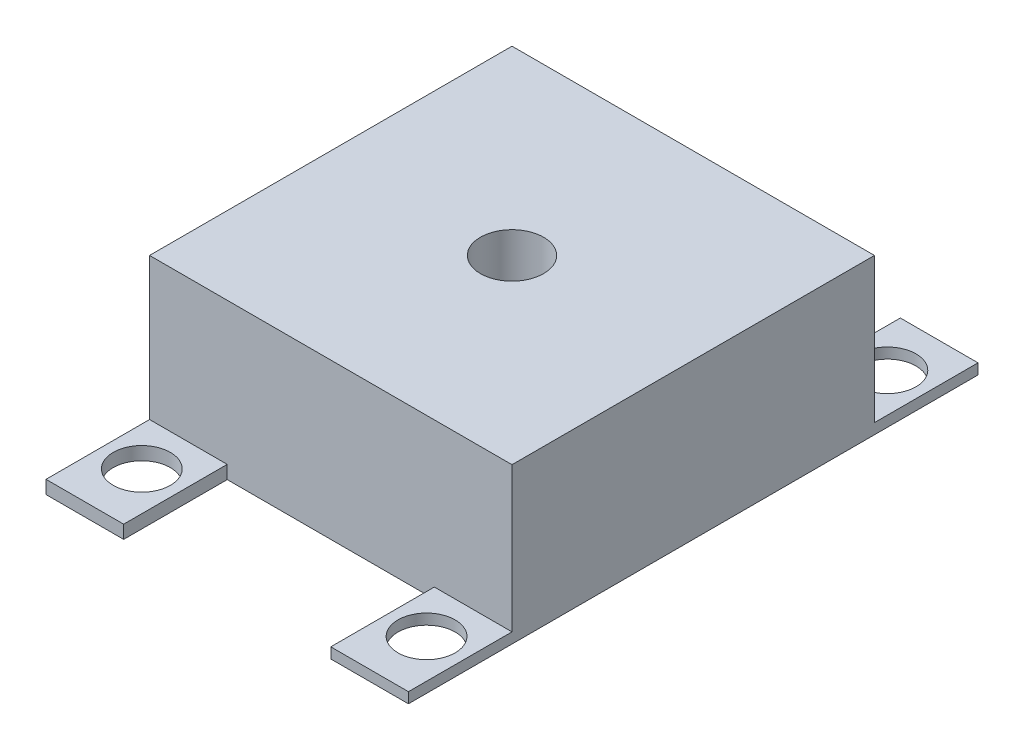
SolidWorks part; units mm, degrees
ref_plane "Front Plane" through (0, 0, 0) normal (0, 0, 1) x (1, 0, 0)
ref_plane "Top Plane" through (0, 0, 0) normal (0, 1, 0) x (1, 0, 0)
ref_plane "Right Plane" through (0, 0, 0) normal (1, 0, 0) x (0, 0, -1)
sketch "Sketch2" plane through (0, 0, 0) normal (0, 1, 0) x (1, 0, 0)
  line L1 (-17.5, 17.5) -> (17.5, 17.5)
  line L2 (-17.5, 17.5) -> (-17.5, -17.5)
  line L3 (-17.5, -17.5) -> (17.5, -17.5)
  line L4 (17.5, 17.5) -> (17.5, -17.5)
  line L5 (-17.5, 17.5) -> (17.5, -17.5) construction
  line L6 (-17.5, -17.5) -> (17.5, 17.5) construction
  point P0 (0, 0)
  dimension "D1" = 35
  dimension "D2" = 35
extrude "Boss-Extrude1" add sketch "Sketch2" along normal blind 10 contours L2 L1 L4 L3
sketch "Sketch3" plane through (0, 10, 0) normal (0, 1, 0) x (1, 0, 0)
  line L1 (-17.5, 17.5) -> (17.5, 17.5)
  line L2 (-17.5, 17.5) -> (-17.5, -17.5)
  line L3 (-17.5, -17.5) -> (17.5, -17.5)
  line L4 (17.5, 17.5) -> (17.5, -17.5)
  line L5 (-17.5, 17.5) -> (17.5, -17.5) construction
  line L6 (-17.5, -17.5) -> (17.5, 17.5) construction
  line L7 (-15, 15) -> (15, 15)
  line L8 (-15, 15) -> (-15, -15)
  line L9 (-15, -15) -> (15, -15)
  line L10 (15, 15) -> (15, -15)
  line L11 (-15, 15) -> (15, -15) construction
  line L12 (-15, -15) -> (15, 15) construction
  point P0 (0, 0)
  point P7 (0, 0)
  dimension "D1" = 30
extrude "Boss-Extrude2" add sketch "Sketch3" along normal blind 15 separate body
sketch "Sketch4" plane through (0, 25, 0) normal (0, 1, 0) x (1, 0, 0)
  line L1 (-17.5, 17.5) -> (17.5, 17.5)
  line L2 (-17.5, 17.5) -> (-17.5, -17.5)
  line L3 (-17.5, -17.5) -> (17.5, -17.5)
  line L4 (17.5, 17.5) -> (17.5, -17.5)
  line L5 (-17.5, 17.5) -> (17.5, -17.5) construction
  line L6 (-17.5, -17.5) -> (17.5, 17.5) construction
  point P0 (0, 0)
extrude "Boss-Extrude3" add sketch "Sketch4" along normal blind 15 separate body
sketch "Sketch5" plane through (0, 40, 0) normal (0, 1, 0) x (1, 0, 0)
  circle A0 centre (0, 0) radius 3.05
extrude "Cut-Extrude1" cut sketch "Sketch5" against normal up to surface (40 mm away)
delete or keep bodies "Body-Delete/Keep 2" type delete bodies bodies 102 104
sketch "Sketch6" plane through (0, 0, -17.5) normal (0, 0, -1) x (-1, 0, 0)
  line L1 (-17.5, 25) -> (-10, 25)
  line L2 (-17.5, 25) -> (-17.5, 26.0178)
  line L3 (-17.5, 26.0178) -> (-10, 26.0178)
  line L4 (-10, 25) -> (-10, 26.0178)
  line L5 (17.5, 25) -> (10, 25)
  line L6 (17.5, 25) -> (17.5, 26.2762)
  line L7 (17.5, 26.2762) -> (10, 26.2762)
  line L8 (10, 25) -> (10, 26.2762)
  dimension "D1" = 7.5
  dimension "D2" = 7.5
extrude "Boss-Extrude4" add sketch "Sketch6" along normal blind 10 and the other way blind 45
sketch "Sketch7" plane through (0, 26.2762, 0) normal (0, 1, 0) x (1, 0, 0)
  line L0 (-17.5, 22.5) -> (-10, 22.5) construction
  line L1 (-17.5, 17.5) -> (-17.5, 27.5) construction
  line L2 (-10, 17.5) -> (-10, 27.5) construction
  circle A0 centre (-13.75, 22.5) radius 2.76
  circle A4 centre (13.75, 22.5) radius 2.76
  circle A5 centre (13.75, -22) radius 2.76
  circle A6 centre (-13.75, -22) radius 2.76
  dimension "D1" = 5.52
  dimension "D2" = 2
  dimension "D3" = 2
extrude "Cut-Extrude2" cut sketch "Sketch7" against normal blind 10
